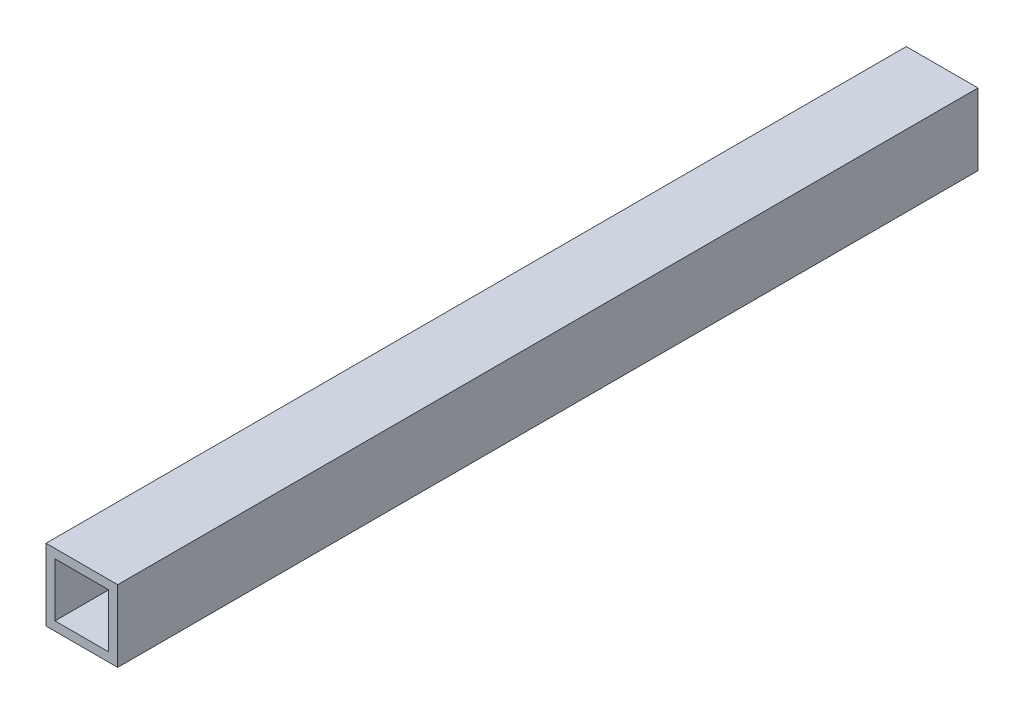
SolidWorks part; units mm, degrees
ref_plane "Front Plane" through (0, 0, 0) normal (0, 0, 1) x (1, 0, 0)
ref_plane "Top Plane" through (0, 0, 0) normal (0, 1, 0) x (1, 0, 0)
ref_plane "Right Plane" through (0, 0, 0) normal (1, 0, 0) x (0, 0, -1)
sketch "Sketch1" plane through (0, 0, 0) normal (0, 0, 1) x (1, 0, 0)
  line L1 (0, 0) -> (25.4, 0)
  line L2 (0, 0) -> (0, -25.4)
  line L3 (0, -25.4) -> (25.4, -25.4)
  line L4 (25.4, 0) -> (25.4, -25.4)
  line L5 (3.175, -3.175) -> (22.225, -3.175)
  line L6 (3.175, -3.175) -> (3.175, -22.225)
  line L7 (3.175, -22.225) -> (22.225, -22.225)
  line L8 (22.225, -3.175) -> (22.225, -22.225)
  dimension "D1" = 25.4
  dimension "D2" = 25.4
  dimension "D3" = 0
  dimension "D4" = 0
  dimension "D5" = 3.175
  dimension "D6" = 3.175
  dimension "D7" = 3.175
  dimension "D8" = 3.175
extrude "Boss-Extrude1" add sketch "Sketch1" along normal blind 304.8
